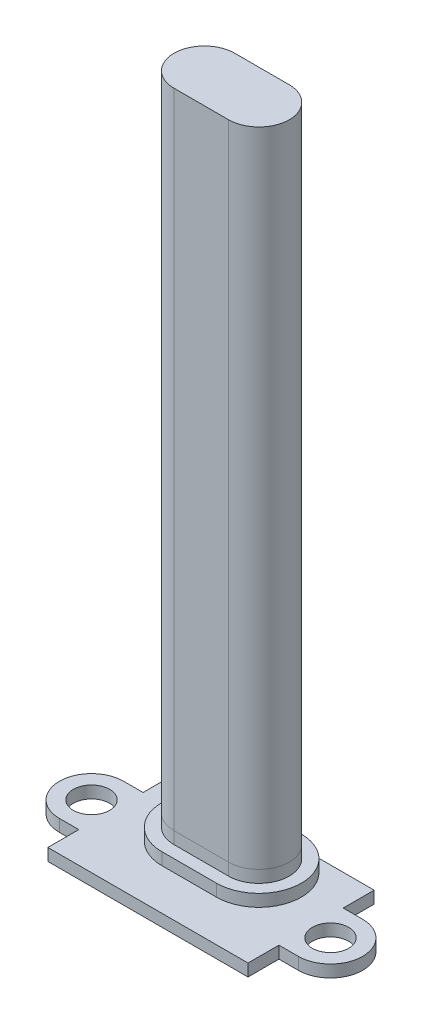
SolidWorks part; units mm, degrees
ref_plane "Front Plane" through (0, 0, 0) normal (0, 0, 1) x (1, 0, 0)
ref_plane "Top Plane" through (0, 0, 0) normal (0, 1, 0) x (1, 0, 0)
ref_plane "Right Plane" through (0, 0, 0) normal (1, 0, 0) x (0, 0, -1)
sketch "Sketch1" plane through (0, 0, 0) normal (0, 1, 0) x (1, 0, 0)
  line L0 (-8.25, 5.2) -> (-9.85, 5.2) construction
  line L1 (-8.25, 0) -> (8.25, 0)
  line L2 (-8.25, 0) -> (-8.25, 2.55)
  line L3 (-8.25, 10.4) -> (8.25, 10.4)
  line L4 (8.25, 0) -> (8.25, 2.55)
  line L5 (8.25, 5.2) -> (9.85, 5.2) construction
  line L6 (-9.85, 7.85) -> (-8.25, 7.85)
  line L7 (-9.85, 2.55) -> (-8.25, 2.55)
  line L8 (-8.25, 7.85) -> (-8.25, 10.4)
  line L9 (8.25, 7.85) -> (8.25, 10.4)
  line L10 (8.25, 7.85) -> (9.85, 7.85)
  line L11 (8.25, 2.55) -> (9.85, 2.55)
  line L12 (-8.25, 7.85) -> (-8.25, 2.55) construction
  line L13 (8.25, 2.55) -> (8.25, 7.85) construction
  circle A0 centre (9.85, 5.2) radius 1.5
  arc A1 (9.85, 2.55) -> (9.85, 7.85) centre (9.85, 5.2) ccw
  circle A2 centre (-9.85, 5.2) radius 1.5
  arc A3 (-9.85, 7.85) -> (-9.85, 2.55) centre (-9.85, 5.2) ccw
  point P10 (12.5, 5.2)
  point P21 (0, 0)
  point P22 (-12.5, 5.2)
  dimension "D3" = 3
  dimension "D4" = 5.3
  dimension "D5" = 25
  dimension "D1" = 16.5
  dimension "D2" = 10.4
extrude "Boss-Extrude1" add sketch "Sketch1" along normal blind 1
sketch "Sketch2" plane through (0, 1, 0) normal (0, 1, 0) x (1, 0, 0)
  line L0 (-2.25, 6.9) -> (2.25, 6.9) construction
  line L1 (-2.25, 10.4) -> (2.25, 10.4)
  line L2 (-2.25, 3.4) -> (2.25, 3.4)
  line L3 (8.25, 10.4) -> (-8.25, 10.4) construction
  line L4 (0, 6.9) -> (0, 0) construction
  line L5 (-8.25, 0) -> (8.25, 0) construction
  arc A0 (-2.25, 10.4) -> (-2.25, 3.4) centre (-2.25, 6.9) ccw
  arc A1 (2.25, 3.4) -> (2.25, 10.4) centre (2.25, 6.9) ccw
  point P2 (0, 6.9)
  point P7 (-5.75, 6.9)
  point P8 (5.75, 6.9)
  dimension "D1" = 7
  dimension "D2" = 11.5
extrude "Boss-Extrude2" add sketch "Sketch2" along normal blind 1 separate body
sketch "Sketch3" plane through (0, 2, 0) normal (0, 1, 0) x (1, 0, 0)
  line L0 (-2.25, 4.4) -> (2.25, 4.4)
  line L1 (2.25, 9.4) -> (-2.25, 9.4)
  line L2 (-2.25, 3.4) -> (2.25, 3.4)
  line L3 (2.25, 10.4) -> (-2.25, 10.4)
  line L4 (-2.25, 3.4) -> (2.25, 3.4) construction
  line L5 (2.25, 10.4) -> (-2.25, 10.4) construction
  arc A0 (-2.25, 9.4) -> (-2.25, 4.4) centre (-2.25, 6.9) ccw
  arc A1 (2.25, 4.4) -> (2.25, 9.4) centre (2.25, 6.9) ccw
  arc A2 (-2.25, 10.4) -> (-2.25, 3.4) centre (-2.25, 6.9) ccw
  arc A3 (2.25, 3.4) -> (2.25, 10.4) centre (2.25, 6.9) ccw
  arc A4 (-2.25, 10.4) -> (-2.25, 3.4) centre (-2.25, 6.9) ccw construction
  arc A5 (2.25, 3.4) -> (2.25, 10.4) centre (2.25, 6.9) ccw construction
  dimension "D1" = 0
  dimension "D2" = 1
extrude "Boss-Extrude4" add sketch "Sketch3" along normal blind 1
sketch "Sketch4" plane through (0, 3, 0) normal (0, 1, 0) x (1, 0, 0)
  line L2 (-2.25, 4.4) -> (2.25, 4.4)
  line L3 (2.25, 9.4) -> (-2.25, 9.4)
  line L4 (-2.25, 4.4) -> (2.25, 4.4)
  line L5 (2.25, 9.4) -> (-2.25, 9.4)
  arc A2 (-2.25, 9.4) -> (-2.25, 4.4) centre (-2.25, 6.9) ccw
  arc A3 (2.25, 4.4) -> (2.25, 9.4) centre (2.25, 6.9) ccw
  arc A4 (-2.25, 9.4) -> (-2.25, 4.4) centre (-2.25, 6.9) ccw
  arc A5 (2.25, 4.4) -> (2.25, 9.4) centre (2.25, 6.9) ccw
  dimension "D1" = 0
extrude "Boss-Extrude5" add sketch "Sketch4" along normal blind 53 separate body
